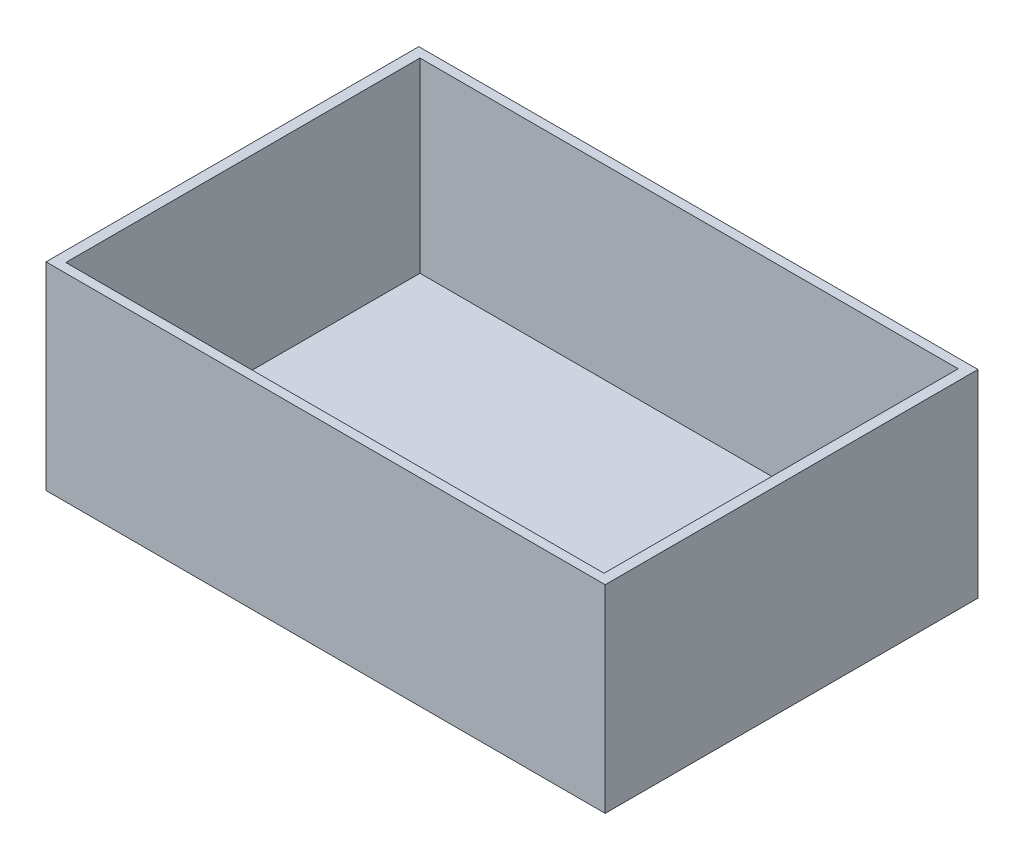
SolidWorks part; units mm, degrees
ref_plane "Plan de face" through (0, 0, 0) normal (0, 0, 1) x (1, 0, 0)
ref_plane "Plan de dessus" through (0, 0, 0) normal (0, 1, 0) x (1, 0, 0)
ref_plane "Plan de droite" through (0, 0, 0) normal (1, 0, 0) x (0, 0, -1)
sketch "Esquisse1" plane through (0, 0, 0) normal (0, 1, 0) x (1, 0, 0)
  line L1 (24, -16) -> (-24, -16)
  line L2 (24, -16) -> (24, 16)
  line L3 (24, 16) -> (-24, 16)
  line L4 (-24, -16) -> (-24, 16)
  line L5 (24, -16) -> (-24, 16) construction
  line L6 (24, 16) -> (-24, -16) construction
  point P0 (0, 0)
  dimension "D1" = 48
  dimension "D2" = 32
extrude "Boss.-Extru.1" add sketch "Esquisse1" along normal blind 17
sketch "Esquisse3" plane through (0, 17, 0) normal (0, 1, 0) x (1, 0, 0)
  line L1 (23.1, -15.2) -> (-23.1, -15.2)
  line L2 (23.1, -15.2) -> (23.1, 15.2)
  line L3 (23.1, 15.2) -> (-23.1, 15.2)
  line L4 (-23.1, -15.2) -> (-23.1, 15.2)
  line L5 (23.1, -15.2) -> (-23.1, 15.2) construction
  line L6 (23.1, 15.2) -> (-23.1, -15.2) construction
  point P0 (0, 0)
  dimension "D1" = 46.2
  dimension "D2" = 30.4
extrude "Enlèv. mat.-Extru.1" cut sketch "Esquisse3" against normal blind 16 contours L3 L4 L1 L2
